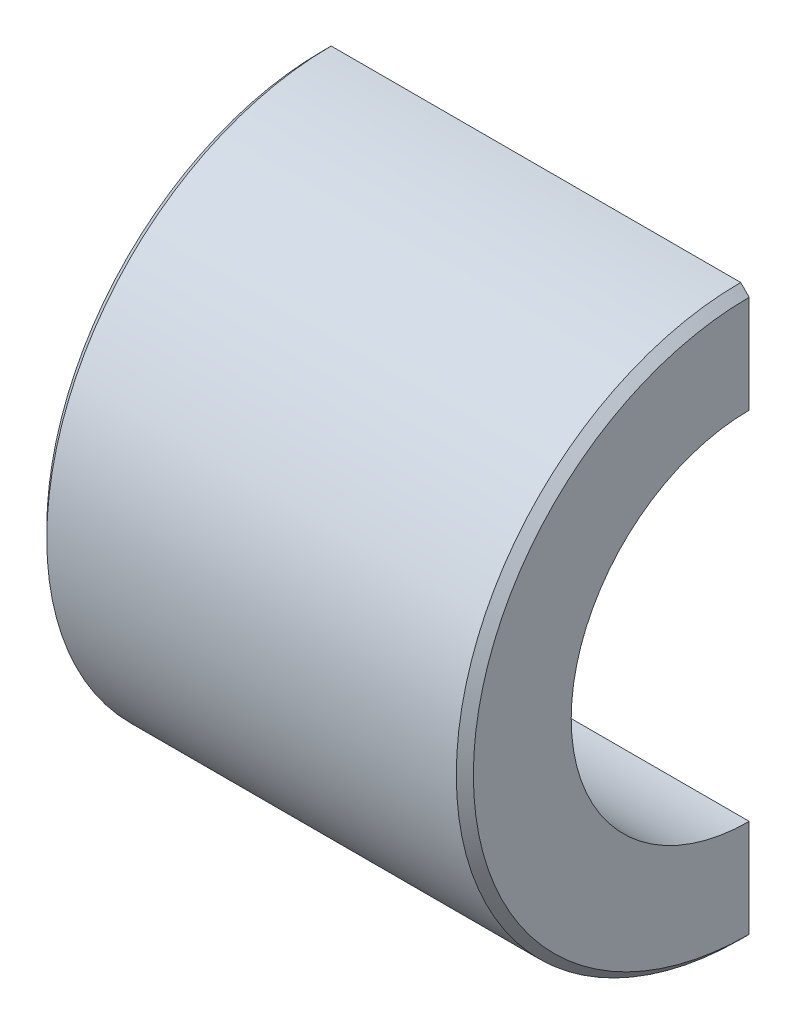
SolidWorks part; units mm, degrees
material "Brass"
ref_plane "Front Plane" through (0, 0, 0) normal (0, 0, 1) x (1, 0, 0)
ref_plane "Top Plane" through (0, 0, 0) normal (0, 1, 0) x (1, 0, 0)
ref_plane "Right Plane" through (0, 0, 0) normal (1, 0, 0) x (0, 0, -1)
sketch "Primary Sketch" plane through (0, 0, 0) normal (0, 0, 1) x (1, 0, 0)
  line L1 (0, 0) -> (19.05, 0) construction
  line L2 (0, 0) -> (0, 12.7) construction
  line L3 (0, 12.7) -> (19.05, 12.7) construction
  line L4 (19.05, 0) -> (19.05, 12.7) construction
  line L5 (0, 7.9502) -> (19.05, 7.9502)
  line L6 (0, 7.9502) -> (0, 12.7)
  line L7 (0, 12.7) -> (19.05, 12.7)
  line L8 (19.05, 7.9502) -> (19.05, 12.7)
  dimension "D1" = 19.05
  dimension "D2" = 7.9502
  dimension "D3" = 12.7
revolve "Primary Revolve" add sketch "Primary Sketch" angle 180 about L1
chamfer "Edge Chamfer" distance 0.381 angle 45 2 edges at (0, 0, 12.7) (19.05, 0, 12.7)
